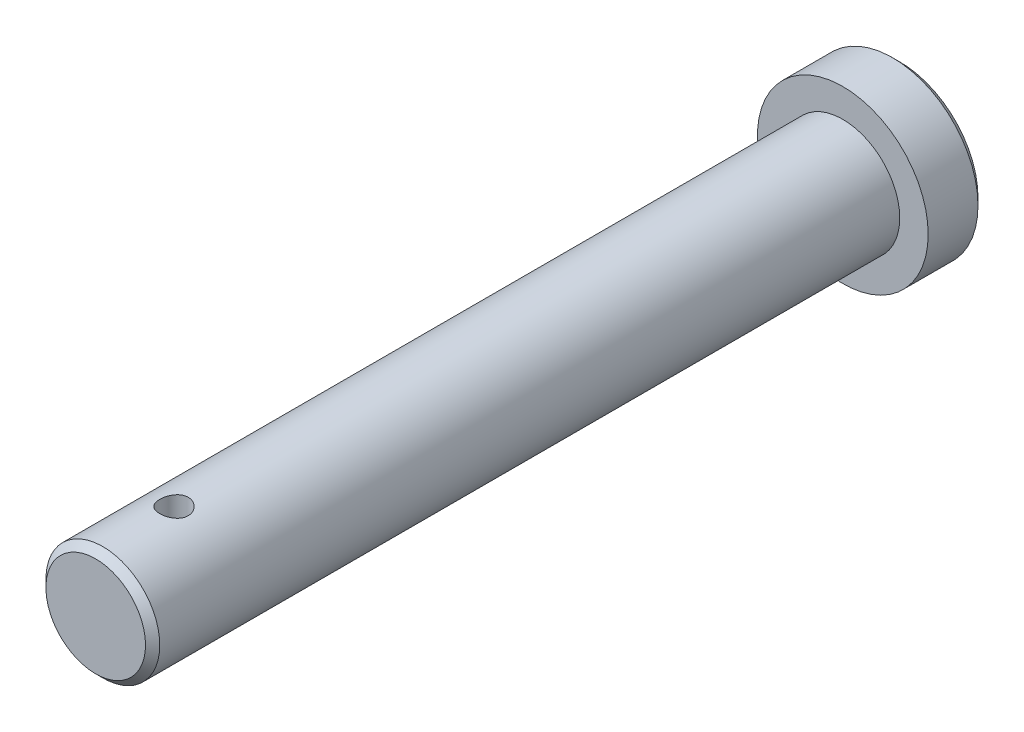
SolidWorks part; units mm, degrees
ref_plane "Front Plane" through (0, 0, 0) normal (0, 0, 1) x (1, 0, 0)
ref_plane "Top Plane" through (0, 0, 0) normal (0, 1, 0) x (1, 0, 0)
ref_plane "Right Plane" through (0, 0, 0) normal (1, 0, 0) x (0, 0, -1)
sketch "Sketch1" plane through (0, 0, 0) normal (0, 0, 1) x (1, 0, 0)
  circle A0 centre (0, 0) radius 12
  dimension "D1" = 24
extrude "Boss-Extrude1" add sketch "Sketch1" along normal blind 8
chamfer "Chamfer2" distance 1 angle 45 1 edges at (12, 0, 0)
sketch "Sketch2" plane through (0, 0, 8) normal (0, 0, 1) x (1, 0, 0)
  circle A0 centre (0, 0) radius 8
  dimension "D1" = 16
extrude "Boss-Extrude2" add sketch "Sketch2" along normal blind 105
chamfer "Chamfer3" distance 1 angle 45 1 edges at (8, 0, 113)
sketch "Sketch3" plane through (0, 0, 0) normal (0, 1, 0) x (1, 0, 0)
  line L0 (-8, -8) -> (8, -8) construction
  circle A0 centre (0, -102) radius 2
  dimension "D1" = 4
  dimension "D2" = 94
extrude "Cut-Extrude1" cut sketch "Sketch3" against normal mid plane 35
